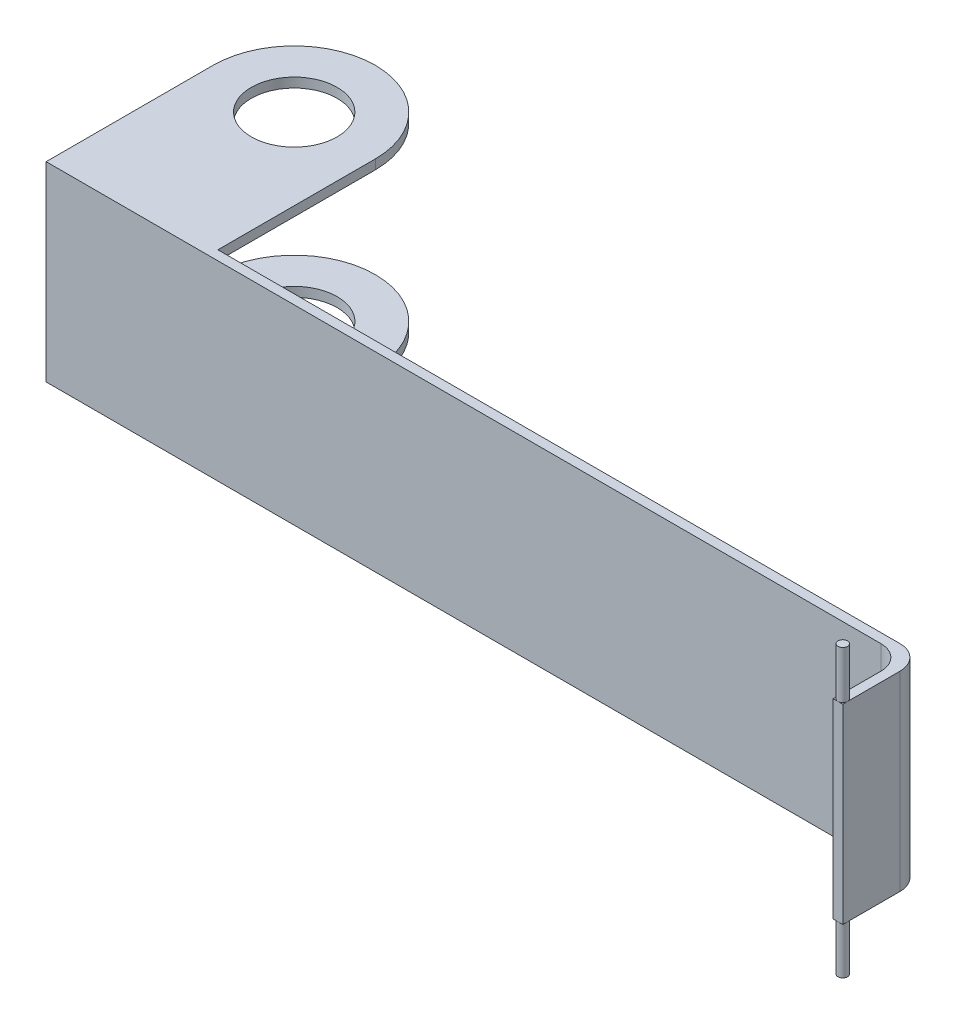
SolidWorks part; units mm, degrees
material "Aleación 1060"
ref_plane "Alzado" through (0, 0, 0) normal (0, 0, 1) x (1, 0, 0)
ref_plane "Planta" through (0, 0, 0) normal (0, 1, 0) x (1, 0, 0)
ref_plane "Vista lateral" through (0, 0, 0) normal (1, 0, 0) x (0, 0, -1)
sketch "Croquis1" plane through (0, 0, 0) normal (0, 1, 0) x (1, 0, 0)
  line L0 (0, 0) -> (17.5, 0)
  line L1 (18, -0.5) -> (18, -1.5)
  line L2 (0, 0) -> (0, 0.2)
  line L3 (0, 0.2) -> (17.7, 0.2)
  line L4 (18, 0.2) -> (18.2, 0.2)
  line L5 (18.2, -0.3) -> (18.2, -1.5)
  line L6 (18.2, -1.5) -> (18, -1.5)
  arc A0 (18, -0.5) -> (17.5, 0) centre (17.5, -0.5) ccw
  arc A1 (18.2, -0.3) -> (17.7, 0.2) centre (17.7, -0.3) ccw
  point P6 (18, 0)
  dimension "D3" = 0.5
  dimension "D6" = 0.5
  dimension "D1" = 18
  dimension "D2" = 1.5
  dimension "D4" = 0.2
  dimension "D5" = 0.2
extrude "Saliente-Extruir1" add sketch "Croquis1" along normal blind 4 contours L5 A1 L3 L2 L0 A0 L1 L6
sketch "Croquis2" plane through (0, 4, 0) normal (0, 1, 0) x (1, 0, 0)
  line L1 (0, 0.2) -> (3.4, 0.2)
  line L2 (0, 0.2) -> (0, 3.5)
  line L4 (3.4, 0.2) -> (3.4, 3.5)
  arc A0 (3.4, 3.5) -> (0, 3.5) centre (1.7, 3.5) ccw
  circle A1 centre (1.7, 3.5) radius 0.9
  dimension "D2" = 1.8
  dimension "D1" = 3.4
extrude "Saliente-Extruir3" add sketch "Croquis2" against normal blind 0.2 contours A0 L2 L1 L4 | A1
sketch "Croquis3" plane through (0, 0, 0) normal (0, -1, 0) x (-1, 0, 0)
  line L1 (0, 0) -> (-3.4, 0)
  line L2 (0, 0) -> (0, 3.5)
  line L4 (-3.4, 0) -> (-3.4, 3.5)
  circle A0 centre (-1.7, 3.5) radius 0.9
  arc A1 (0, 3.5) -> (-3.4, 3.5) centre (-1.7, 3.5) ccw
  dimension "D3" = 1.8
  dimension "D4" = 3.4
  dimension "D1" = 3.4
extrude "Saliente-Extruir4" add sketch "Croquis3" against normal blind 0.2
sketch "Croquis4" plane through (0, 4, 0) normal (0, 1, 0) x (1, 0, 0)
  line L0 (18.2, -1.5) -> (18, -1.5) construction
  circle A0 centre (18.1, -1.4) radius 0.1
  dimension "D1" = 0.1
extrude "Saliente-Extruir5" add sketch "Croquis4" along normal blind 1 contours A0
sketch "Croquis5" plane through (0, 0, 0) normal (0, -1, 0) x (-1, 0, 0)
  line L0 (-18.2, -1.5) -> (-18, -1.5) construction
  circle A0 centre (-18.1, -1.4) radius 0.1
  dimension "D1" = 0.2
  dimension "D2" = 0.1
extrude "Saliente-Extruir6" add sketch "Croquis5" along normal blind 1
